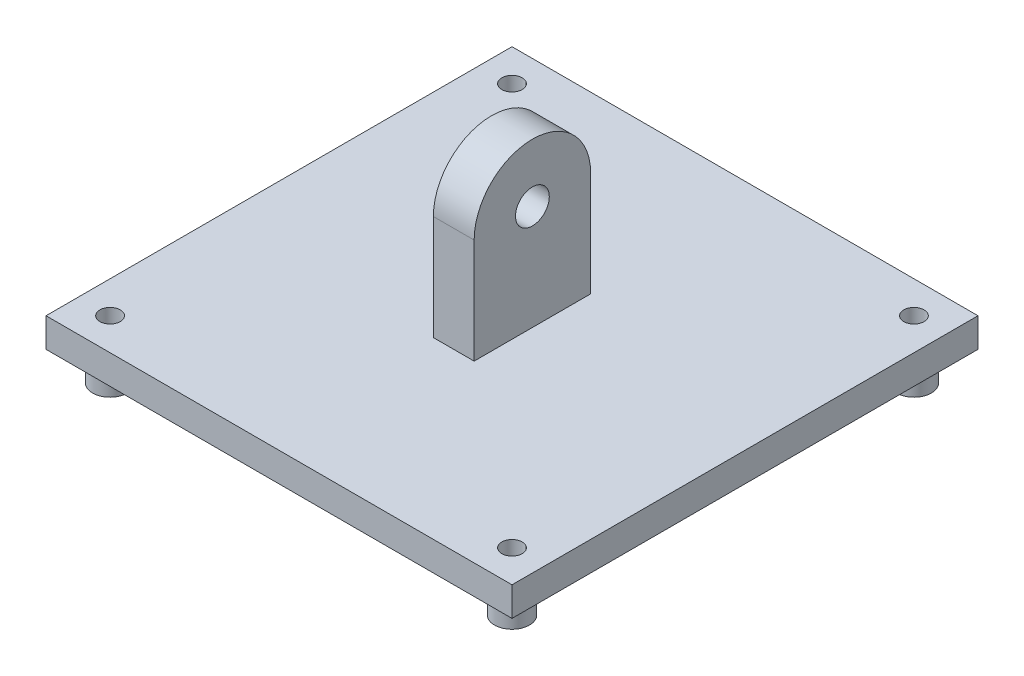
SolidWorks part; units mm, degrees
ref_plane "Front Plane" through (0, 0, 0) normal (0, 0, 1) x (1, 0, 0)
ref_plane "Top Plane" through (0, 0, 0) normal (0, 1, 0) x (1, 0, 0)
ref_plane "Right Plane" through (0, 0, 0) normal (1, 0, 0) x (0, 0, -1)
sketch "Sketch2" plane through (0, 0, 0) normal (0, 1, 0) x (1, 0, 0)
  line L1 (-40, -40) -> (40, -40)
  line L2 (-40, -40) -> (-40, 40)
  line L3 (-40, 40) -> (40, 40)
  line L4 (40, -40) -> (40, 40)
  line L5 (-40, -40) -> (40, 40) construction
  line L6 (-40, 40) -> (40, -40) construction
  point P0 (0, 0)
  dimension "D1" = 80
  dimension "D2" = 80
extrude "Boss-Extrude1" add sketch "Sketch2" along normal blind 5
sketch "Sketch9" plane through (0, 0, 0) normal (0, -1, 0) x (1, 0, 0)
  line L0 (0, 0) -> (0, -40)
  line L1 (40, -40) -> (-40, -40) construction
  circle A0 centre (-34.5, 34.5) radius 3
  circle A1 centre (34.5, 34.5) radius 3
  circle A2 centre (-34.5, -34.5) radius 3
  circle A3 centre (34.5, -34.5) radius 3
  dimension "D2" = 34.5
  dimension "D3" = 6
  dimension "D5" = 34.5
  dimension "D1" = 34.5
  dimension "D4" = 34.5
extrude "Boss-Extrude3" add sketch "Sketch9" along normal blind 5 contours A0 | A1 | A3 | A2
sketch "Sketch10" plane through (0, -5, 0) normal (0, -1, 0) x (1, 0, 0)
  circle A0 centre (-34.5, -34.5) radius 1.75
  circle A1 centre (-34.5, 34.5) radius 1.75
  circle A2 centre (34.5, 34.5) radius 1.75
  circle A3 centre (34.5, -34.5) radius 1.75
  dimension "D1" = 3.5
extrude "Cut-Extrude6" cut sketch "Sketch10" against normal through all
sketch "Sketch11" plane through (40, 0, 0) normal (1, 0, 0) x (0, 0, -1)
  line L0 (-10, 5) -> (-10, 23)
  line L1 (-40, 5) -> (40, 5) construction
  line L2 (-10, 5) -> (10, 5)
  line L3 (10, 5) -> (10, 23)
  arc A0 (10, 23) -> (-10, 23) centre (0, 23) ccw
  circle A1 centre (0, 23) radius 2.9
  point P8 (0, 5)
  dimension "D2" = 18
  dimension "D3" = 5.8
  dimension "D1" = 20
extrude "Boss-Extrude4" add sketch "Sketch11" against normal up to surface (80 mm away) up to face at (-40, 2.5, 0)
sketch "Sketch12" plane through (0, 5, 0) normal (0, 1, 0) x (1, 0, 0)
  line L0 (-3.5, -10) -> (3.5, -10)
  line L1 (-40, -10) -> (40, -10) construction
  line L2 (3.5, -10) -> (3.5, 10)
  line L3 (-40, 10) -> (40, 10) construction
  line L4 (3.5, 10) -> (-3.5, 10)
  line L5 (-3.5, 10) -> (-3.5, -10)
  line L6 (40, 40) -> (-40, 40)
  line L7 (-40, 40) -> (-40, -40)
  line L8 (-40, -40) -> (40, -40)
  line L9 (40, -40) -> (40, 40)
  point P14 (0, 10)
  dimension "D1" = 7
extrude "Cut-Extrude7" cut sketch "Sketch12" along normal through all
